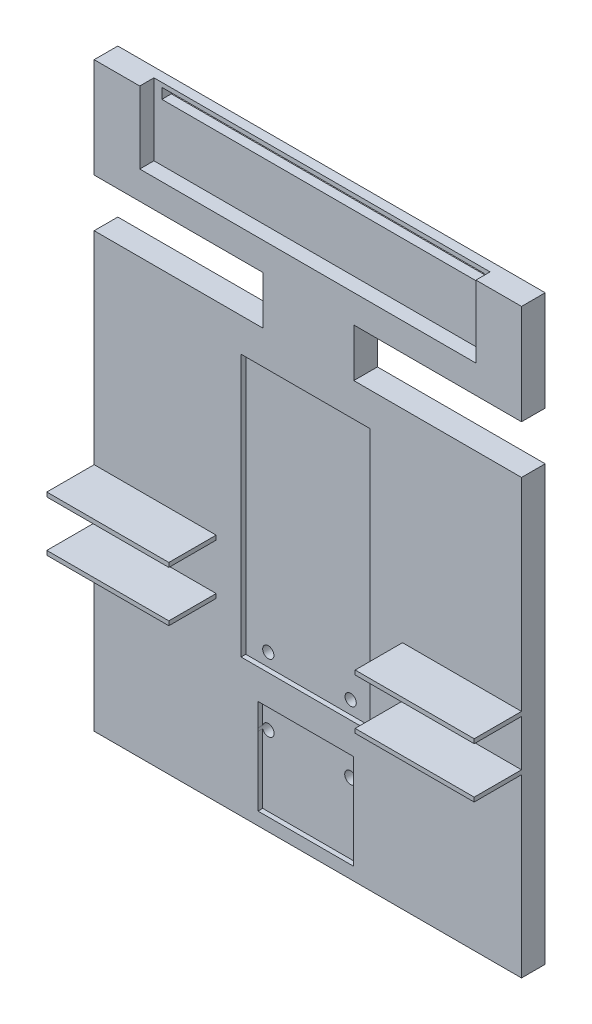
SolidWorks part; units mm, degrees
ref_plane "Plano frontal" through (0, 0, 0) normal (0, 0, 1) x (1, 0, 0)
ref_plane "Plano superior" through (0, 0, 0) normal (0, 1, 0) x (1, 0, 0)
ref_plane "Plano direito" through (0, 0, 0) normal (1, 0, 0) x (0, 0, -1)
sketch "Esboço1" plane through (0, 0, 0) normal (0, 0, 1) x (1, 0, 0)
  line L0 (-44.6735, 40.7151) -> (-44.6735, 19.6036)
  line L1 (-44.6735, 40.7151) -> (45.616, 40.7151)
  line L2 (45.616, 40.7151) -> (45.616, 19.6036)
  line L3 (-44.6735, 19.6036) -> (-9.0478, 19.6036)
  line L4 (45.616, 19.6036) -> (10.1788, 19.6036)
  line L5 (10.1788, 19.6036) -> (10.1788, 9.4248)
  line L6 (-9.0478, 19.6036) -> (-9.0478, 9.4248)
  line L7 (-9.0478, 9.4248) -> (-44.6735, 9.4248)
  line L8 (10.1788, 9.4248) -> (45.616, 9.4248)
  line L9 (-44.6735, 9.4248) -> (-44.6735, -71.4399)
  line L10 (-44.6735, -71.4399) -> (45.616, -71.4399)
  line L11 (45.616, -71.4399) -> (45.616, 9.4248)
extrude "Ressalto-extrusão1" add sketch "Esboço1" along normal blind 5
sketch "Esboço2" plane through (0, 0, 5) normal (0, 0, 1) x (1, 0, 0)
  line L0 (-35.0374, 25.5264) -> (35.9799, 25.5264)
  line L1 (45.616, 40.7151) -> (-44.6735, 40.7151) construction
  line L2 (-35.0374, 40.7151) -> (35.9799, 40.7151)
  line L4 (35.9799, 25.5264) -> (35.9799, 40.7151)
  line L5 (-35.0374, 25.5264) -> (-35.0374, 40.7151)
extrude "Corte-extrusão1" cut sketch "Esboço2" against normal blind 3
ref_plane "Plano1" through (-35.0374, 40.7151, 5) normal (0, -1, 0) x (-1, 0, 0)
ref_plane "Plano2" through (-44.6735, -71.4399, 5) normal (0, -1, 0) x (-1, 0, 0)
other "Mover face1" face at (0.4712, -71.4399, 2.5) parameters "D1"=10.7189
sketch "Esboço3" plane through (0, 0, 2) normal (0, 0, 1) x (1, 0, 0)
  line L0 (34.723, 39.8114) -> (-33.3668, 39.8114)
  line L3 (-33.3668, 39.8114) -> (-33.3668, 37.6066)
  line L4 (-33.3668, 37.6066) -> (34.723, 37.6066)
  line L5 (34.723, 37.6066) -> (34.723, 39.8114)
extrude "Corte-extrusão2" cut sketch "Esboço3" against normal blind 10 contours L3 L4 L5 L0
sketch "Esboço4" plane through (0, 0, 5) normal (0, 0, 1) x (1, 0, 0)
  line L0 (-9.0478, 9.4248) -> (-9.0478, 2.3501)
  line L3 (13.645, 2.3501) -> (13.645, -53.0563)
  line L4 (13.645, -53.0563) -> (-13.6372, -53.0563)
  line L5 (-13.6372, -53.0563) -> (-13.6372, 2.3501)
  line L6 (-10.0638, -59.3844) -> (10.0672, -59.3844)
  line L7 (-13.6372, 2.3501) -> (13.645, 2.3501)
  line L8 (-44.6735, -46.0075) -> (-25.2937, -46.0075)
  line L9 (-10.0638, -59.3844) -> (-10.0638, -79.4588)
  line L10 (-10.0638, -79.4588) -> (10.0672, -79.4588)
  line L11 (10.0672, -79.4588) -> (10.0672, -59.3844)
  line L12 (-44.6735, 9.4248) -> (-44.6735, -82.1588) construction
  line L13 (45.616, -46.0075) -> (26.2451, -46.0075)
  line L14 (45.616, -82.1588) -> (45.616, 9.4248) construction
  line L15 (26.2451, -46.0075) -> (26.2451, -55.4725)
  line L16 (26.2451, -55.4725) -> (45.616, -55.4725)
  line L17 (45.616, -55.4725) -> (45.616, -46.0075)
extrude "Corte-extrusão4" cut sketch "Esboço4" against normal blind 1 contours L10 L11 L6 L9 | L7 L3 L4 L5
sketch "Esboço5" plane through (0, 0, 0) normal (0, 0, -1) x (-1, 0, 0)
  line L0 (-10.1084, -65.8553) -> (10.4374, -65.8553)
  line L3 (10.4374, -65.8553) -> (10.4374, -48.8461)
  line L5 (10.4374, -48.8461) -> (-10.1084, -48.8461)
  line L6 (-10.1084, -48.8461) -> (-10.1084, -65.8553)
  circle A0 centre (-8.5176, -50.2919) radius 1.1882
  circle A1 centre (-8.5176, -64.5501) radius 1.2581
  circle A2 centre (8.8858, -64.5501) radius 1.2206
  circle A3 centre (8.8858, -50.2919) radius 1.1882
extrude "Corte-extrusão5" cut sketch "Esboço5" against normal blind 10 contours A0 | A3 | A1 | A2
sketch "Esboço6" plane through (0, 0, 5) normal (0, 0, 1) x (1, 0, 0)
  line L0 (45.616, -44.9671) -> (20.4673, -44.9671)
  line L1 (45.616, -82.1588) -> (45.616, 9.4248) construction
  line L2 (20.4673, -44.9671) -> (20.4673, -33.3844)
  line L3 (20.4673, -33.3844) -> (45.616, -33.3844)
  line L4 (45.616, -33.3844) -> (45.616, -44.9671)
  line L5 (-44.6735, -33.3844) -> (-18.8945, -33.3844)
  line L6 (-44.6735, 9.4248) -> (-44.6735, -82.1588) construction
  line L7 (-18.8945, -33.3844) -> (-18.8945, -44.9671)
  line L8 (-18.8945, -44.9671) -> (-44.6735, -44.9671)
  line L9 (-44.6735, -44.9671) -> (-44.6735, -33.3844)
extrude "Ressalto-extrusão2" add sketch "Esboço6" along normal blind 10
sketch "Esboço7" plane through (45.616, 0, 0) normal (1, 0, 0) x (0, 0, -1)
  line L0 (-5, -34.2971) -> (-5, -44.0667)
  line L3 (-5, -44.0667) -> (-15, -44.0667)
  line L4 (-15, -44.9671) -> (-15, -33.3844) construction
  line L5 (-15, -34.2971) -> (-15, -44.0667)
  line L6 (-15, -34.2971) -> (-5, -34.2971)
extrude "Corte-extrusão7" cut sketch "Esboço7" against normal blind 99
